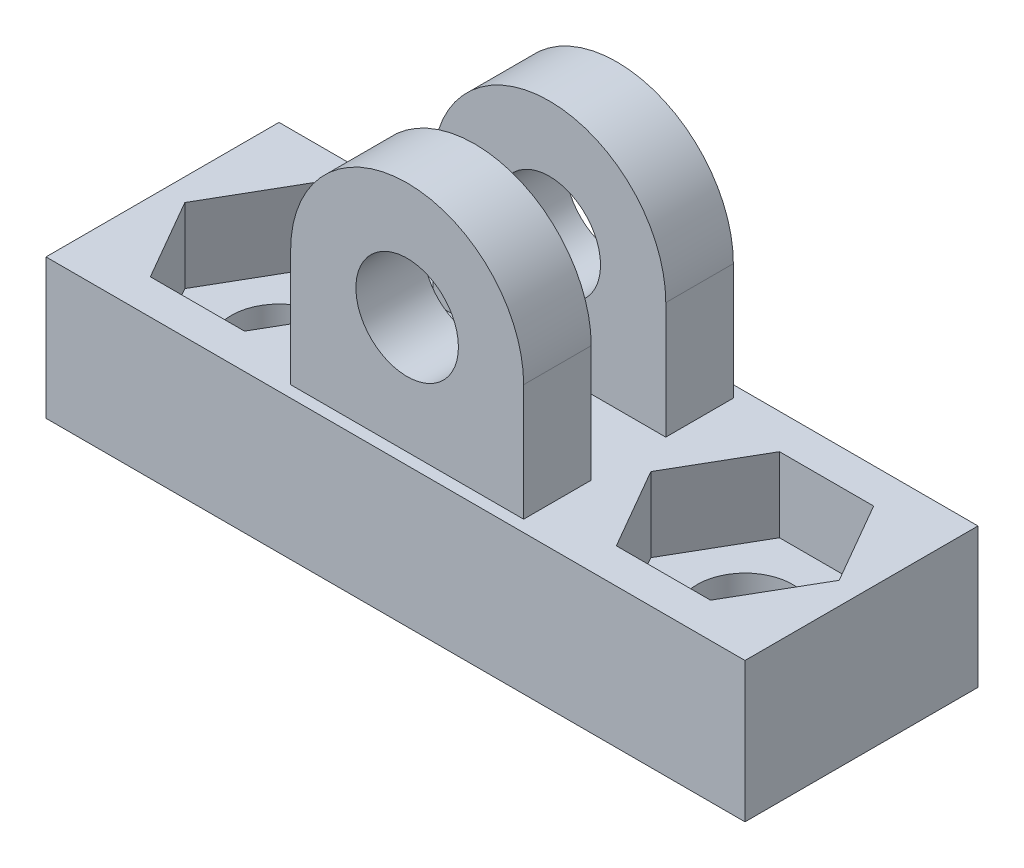
SolidWorks part; units mm, degrees
ref_plane "Front Plane" through (0, 0, 0) normal (0, 0, 1) x (1, 0, 0)
ref_plane "Top Plane" through (0, 0, 0) normal (0, 1, 0) x (1, 0, 0)
ref_plane "Right Plane" through (0, 0, 0) normal (1, 0, 0) x (0, 0, -1)
sketch "Sketch1" plane through (0, 0, 0) normal (0, 1, 0) x (1, 0, 0)
  line L1 (-5, -5) -> (5, -5)
  line L2 (-5, -5) -> (-5, 5)
  line L3 (-5, 5) -> (5, 5)
  line L4 (5, -5) -> (5, 5)
  line L5 (-5, -5) -> (5, 5) construction
  line L6 (-5, 5) -> (5, -5) construction
  circle A0 centre (0, 0) radius 2.05
  point P0 (0, 0)
  dimension "D3" = 4.1
  dimension "D1" = 10
  dimension "D2" = 10
extrude "Boss-Extrude1" add sketch "Sketch1" along normal blind 6
sketch "Sketch2" plane through (0, 6, 0) normal (0, 1, 0) x (1, 0, 0)
  line L1 (4.0415, 0) -> (2.0207, 3.5)
  line L2 (2.0207, 3.5) -> (-2.0207, 3.5)
  line L3 (-2.0207, 3.5) -> (-4.0415, 0)
  line L4 (-4.0415, 0) -> (-2.0207, -3.5)
  line L5 (-2.0207, -3.5) -> (2.0207, -3.5)
  line L6 (2.0207, -3.5) -> (4.0415, 0)
  circle A0 centre (0, 0) radius 3.5 construction
  dimension "D1" = 7
extrude "Cut-Extrude1" cut sketch "Sketch2" against normal blind 3.2
sketch "Sketch3" plane through (5, 0, 0) normal (1, 0, 0) x (0, 0, -1)
  line L0 (5, 6) -> (5, 0) construction
  line L1 (-5, 6) -> (5, 6)
  line L2 (-5, 6) -> (-5, 0)
  line L3 (-5, 0) -> (5, 0)
  line L4 (5, 6) -> (5, 0)
  line L5 (-5, 0) -> (5, 0) construction
extrude "Boss-Extrude2" add sketch "Sketch3" along normal blind 20
sketch "Sketch4" plane through (0, 6, 0) normal (0, 1, 0) x (1, 0, 0)
  circle A0 centre (20, 0) radius 2.05
  dimension "D2" = 4.1
  dimension "D1" = 20
extrude "Cut-Extrude2" cut sketch "Sketch4" against normal through all
sketch "Sketch5" plane through (0, 6, 0) normal (0, 1, 0) x (1, 0, 0)
  line L1 (24.0415, 0) -> (22.0207, 3.5)
  line L2 (22.0207, 3.5) -> (17.9793, 3.5)
  line L3 (17.9793, 3.5) -> (15.9585, 0)
  line L4 (15.9585, 0) -> (17.9793, -3.5)
  line L5 (17.9793, -3.5) -> (22.0207, -3.5)
  line L6 (22.0207, -3.5) -> (24.0415, 0)
  circle A0 centre (20, 0) radius 3.5 construction
  dimension "D1" = 7
extrude "Cut-Extrude3" cut sketch "Sketch5" against normal blind 3.2
ref_plane "Plane1" through (0, 0, 0) normal (0, 0, 1) x (1, 0, 0)
sketch "Sketch8" plane through (0, 0, 0) normal (0, 0, 1) x (1, 0, 0)
  line L0 (-5, 2.2269) -> (25, 2.2269) construction
  line L1 (-5, 6) -> (-5, 0) construction
  line L2 (25, 6) -> (25, 0) construction
  line L3 (10, 14.4251) -> (10, 2.2269) construction
  line L4 (5, 6) -> (5, 11)
  line L5 (15, 6) -> (15, 11)
  line L6 (-5, 6) -> (25, 6) construction
  line L7 (15, 6) -> (5, 6)
  line L8 (24.0415, 6) -> (22.0207, 6) construction
  circle A0 centre (10, 11) radius 2.2
  arc A1 (15, 11) -> (5, 11) centre (10, 11) ccw
  point P10 (0, 0)
  point P13 (0, 0)
  point P20 (0, 0)
  point P21 (0, 0)
  point P22 (0, 0)
  point P23 (5, 11)
  point P24 (0, 0)
  dimension "D1" = 4.4
  dimension "D2" = 5
extrude "Boss-Extrude4" add sketch "Sketch8" along normal mid plane 9
sketch "Sketch10" plane through (0, 0, 0) normal (0, 0, 1) x (1, 0, 0)
  line L0 (-5, 6) -> (25, 6) construction
  line L1 (20.0692, 6) -> (2.8146, 6)
  line L2 (20.0692, 6) -> (20.0692, 18.2528)
  line L3 (20.0692, 18.2528) -> (2.8146, 18.2528)
  line L4 (2.8146, 6) -> (2.8146, 18.2528)
extrude "Cut-Extrude5" cut sketch "Sketch10" against normal mid plane 3.2
equation "\"A\"=1.7"
